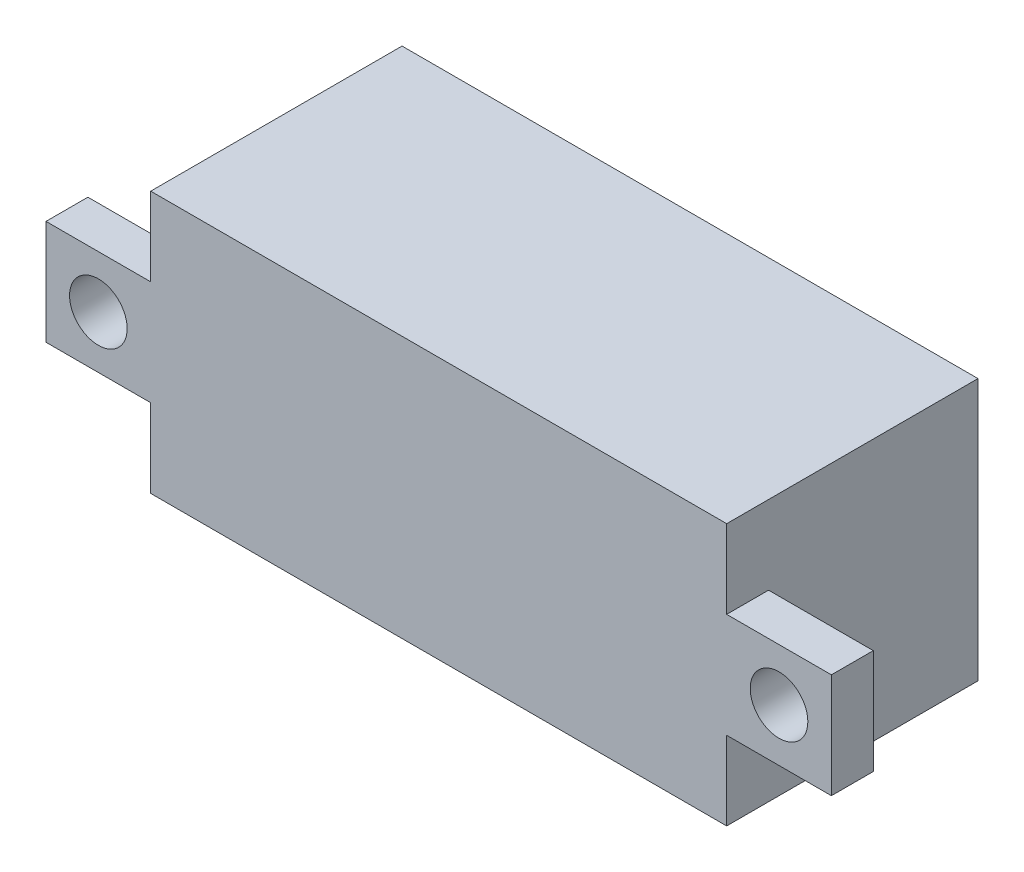
SolidWorks part; units mm, degrees
ref_plane "前视基准面" through (0, 0, 0) normal (0, 0, 1) x (1, 0, 0)
ref_plane "上视基准面" through (0, 0, 0) normal (0, 1, 0) x (1, 0, 0)
ref_plane "右视基准面" through (0, 0, 0) normal (1, 0, 0) x (0, 0, -1)
other "Configuration Table"
sketch "草图1" plane through (0, 0, 0) normal (0, 0, 1) x (1, 0, 0)
  line L1 (0, 0) -> (22, 0)
  line L2 (0, 0) -> (0, 10)
  line L3 (0, 10) -> (22, 10)
  line L4 (22, 0) -> (22, 10)
  dimension "D1" = 22
  dimension "D2" = 10
extrude "凸台-拉伸1" add sketch "草图1" along normal blind 8
sketch "草图2" plane through (0, 0, 8) normal (0, 0, 1) x (1, 0, 0)
  line L0 (0, 10) -> (0, 0) construction
  line L1 (0, 7) -> (-4, 7)
  line L3 (0, 3) -> (-4, 3)
  line L4 (-4, 7) -> (-4, 3)
  line L5 (22, 0) -> (22, 10) construction
  line L6 (22, 7) -> (26, 7)
  line L8 (22, 3) -> (26, 3)
  line L9 (26, 7) -> (26, 3)
  line L10 (22, 10) -> (0, 10) construction
  line L11 (0, 0) -> (22, 0) construction
  line L12 (-4, 5) -> (26, 5) construction
  line L13 (0, 3) -> (0, 0)
  line L14 (0, 0) -> (22, 0)
  line L15 (22, 0) -> (22, 3)
  line L16 (22, 7) -> (22, 10)
  line L17 (22, 10) -> (0, 10)
  line L18 (0, 10) -> (0, 7)
  circle A0 centre (-2, 5) radius 1.1
  circle A1 centre (24, 5) radius 1.1
  dimension "D9" = 2.2
  dimension "D10" = 2.2
  dimension "D1" = 3
  dimension "D2" = 3
  dimension "D3" = 3
  dimension "D4" = 3
  dimension "D5" = 4
  dimension "D6" = 4
  dimension "D7" = 2
  dimension "D8" = 2
extrude "凸台-拉伸2" add sketch "草图2" along normal blind 1.6
